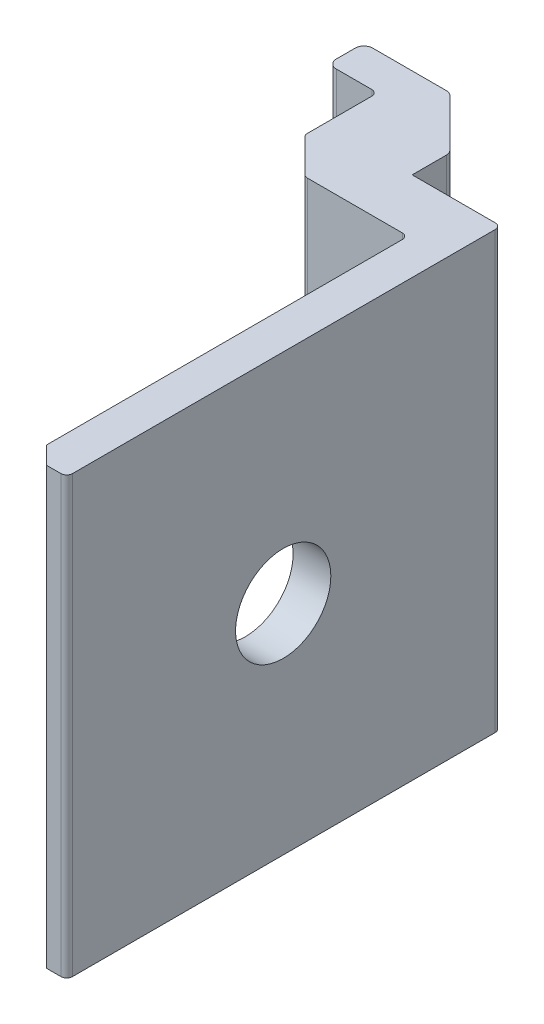
SolidWorks part; units mm, degrees
ref_plane "Front Plane" through (0, 0, 0) normal (0, 0, 1) x (1, 0, 0)
ref_plane "Top Plane" through (0, 0, 0) normal (0, 1, 0) x (1, 0, 0)
ref_plane "Right Plane" through (0, 0, 0) normal (1, 0, 0) x (0, 0, -1)
sketch "Sketch1" plane through (0, 0, 0) normal (0, 1, 0) x (1, 0, 0)
  line L0 (-12.2369, 8.0695) -> (-15.3865, 8.0695)
  line L1 (-15.3865, 8.0695) -> (-15.3865, -1.4555)
  line L2 (-15.3865, -1.4555) -> (-12.2115, -4.6305)
  line L3 (-12.2115, -4.6305) -> (-3.1945, -4.6305)
  line L4 (-3.1945, -4.6305) -> (-3.1945, -36.2637)
  line L5 (-3.1945, -36.2637) -> (-1.6705, -37.7877)
  line L6 (-1.6705, -37.7877) -> (0.1075, -37.7877)
  line L7 (0.1075, -37.7877) -> (0.1075, 0.1955)
  line L8 (0.1075, 0.1955) -> (-7.6649, 0.1955)
  line L9 (-7.6649, 0.1955) -> (-7.6649, 3.4975)
  line L10 (-7.6649, 3.4975) -> (-12.2369, 8.0695)
extrude "Boss-Extrude1" add sketch "Sketch1" against normal blind 38.1
sketch "Sketch2" plane through (-15.3865, 0, 0) normal (-1, 0, 0) x (0, 0, 1)
  line L0 (-4.8945, -38.1) -> (-8.0695, -38.1)
  line L1 (-8.0695, -38.1) -> (-8.0695, 0)
  line L2 (-8.0695, 0) -> (-4.8945, 0)
  line L3 (-4.8945, 0) -> (-4.8945, -38.1)
extrude "Boss-Extrude2" add sketch "Sketch2" along normal blind 4.3688
hole_wizard "Hole1" positions "Sketch4" profile "Sketch3" legacy
sketch "Sketch4" plane through (0.1075, 0, 0) normal (1, 0, 0) x (0, 0, -1)
  point P0 (-18.8545, -19.05)
sketch "Sketch3" plane through (0.1075, -19.05, 18.8545) normal (0, 1, 0) x (0, 0, -1)
  line L0 (0, 0) -> (0, 19.8628)
  line L1 (0, 19.8628) -> (4.1656, 19.8628)
  line L2 (4.1656, 19.8628) -> (4.1656, 0)
  line L3 (4.1656, 0) -> (0, 0)
  line L4 (0, 110) -> (0, -10) construction
  dimension "Diameter" = 8.3312
  dimension "Depth" = 19.8628
fillet "Fillet1" radius 0.508 6 edges at (0.1075, -19.05, -0.1955) (0.1075, -19.05, 37.7877) (-12.2115, -19.05, 4.6305) (-3.1945, -19.05, 4.6305) (-15.3865, -19.05, 1.4555)
fillet "Fillet2" radius 0.762 4 edges at (-7.6649, -19.05, -3.4975) (-19.7553, -19.05, -4.8945) (-19.7553, -19.05, -8.0695) (-12.2369, -19.05, -8.0695)
